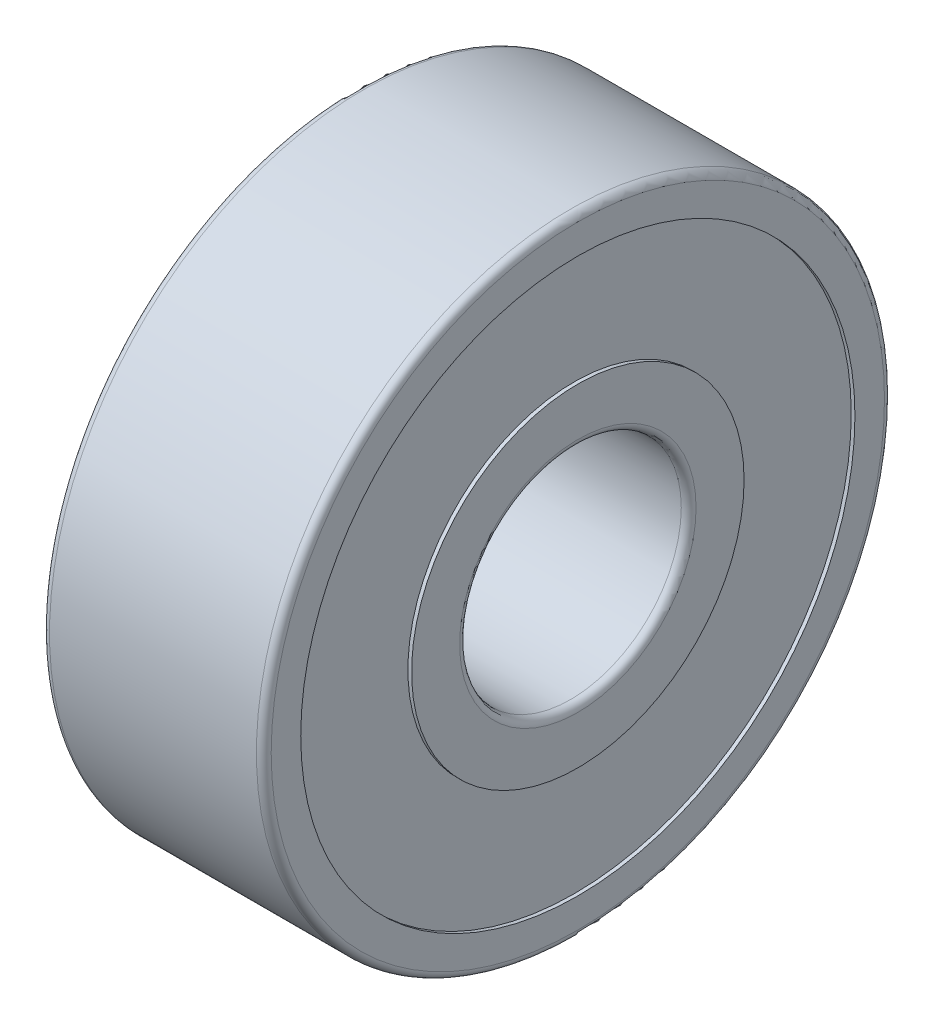
SolidWorks part; units mm, degrees
ref_plane "Front Plane" through (0, 0, 0) normal (0, 0, 1) x (1, 0, 0)
ref_plane "Top Plane" through (0, 0, 0) normal (0, 1, 0) x (1, 0, 0)
ref_plane "Right Plane" through (0, 0, 0) normal (1, 0, 0) x (0, 0, -1)
sketch "Sketch1" plane through (0, 0, 0) normal (1, 0, 0) x (0, 0, -1)
  circle A0 centre (0, 0) radius 8.5
  circle A1 centre (0, 0) radius 3
  dimension "D1" = 17
  dimension "D2" = 6
extrude "Boss-Extrude1" add sketch "Sketch1" along normal blind 6
sketch "Sketch2" plane through (6, 0, 0) normal (1, 0, 0) x (0, 0, -1)
  circle A0 centre (0, 0) radius 4.5
  circle A1 centre (0, 0) radius 7.5
  circle A2 centre (0, 0) radius 8.5 construction
  circle A3 centre (0, 0) radius 3 construction
  dimension "D1" = 1
  dimension "D2" = 1.5
extrude "Cut-Extrude1" cut sketch "Sketch2" against normal blind 0.1
sketch "Sketch3" plane through (0, 0, 0) normal (-1, 0, 0) x (0, 0, 1)
  circle A1 centre (0, 0) radius 7.5
  circle A2 centre (0, 0) radius 7.5
  circle A3 centre (0, 0) radius 4.5
  circle A4 centre (0, 0) radius 4.5
  dimension "D1" = 0
  dimension "D2" = 0
extrude "Cut-Extrude2" cut sketch "Sketch3" against normal blind 0.1
fillet "Fillet1" radius 0.2 4 edges at (6, 0, -3) (6, 0, -8.5) (0, 0, -3) (0, 0, -8.5)
